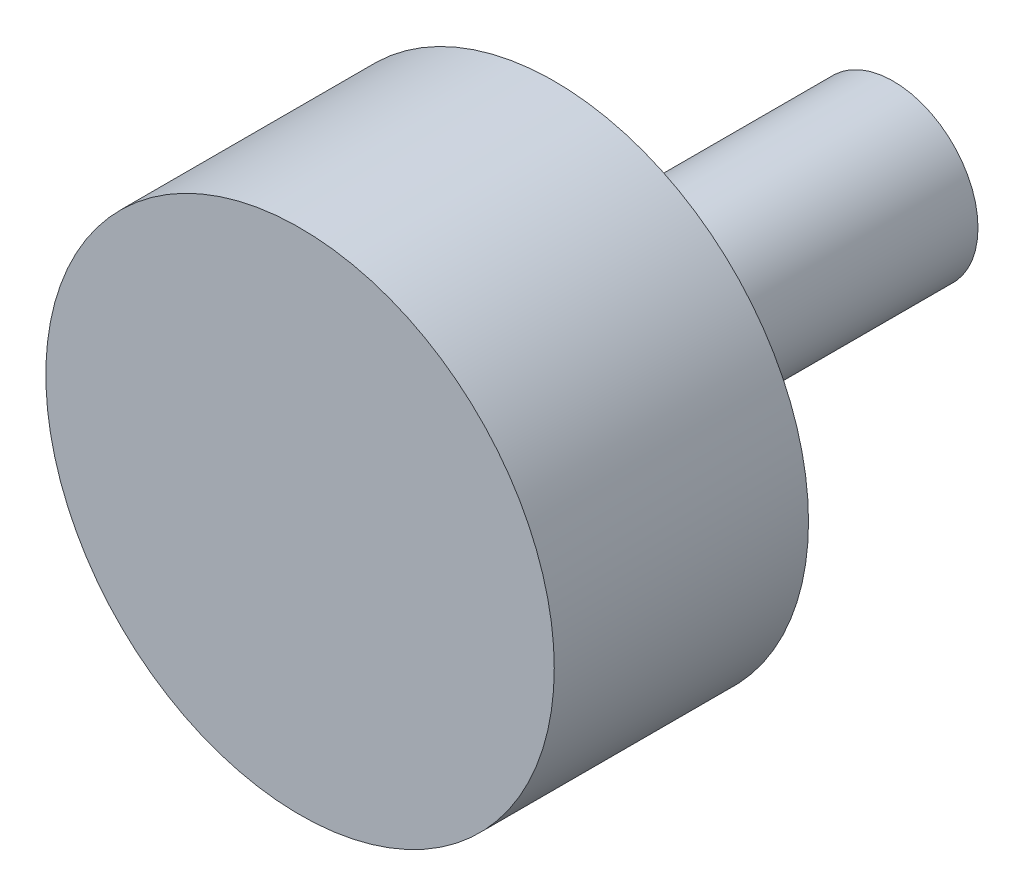
SolidWorks part; units mm, degrees
material "AISI 1035 Steel (SS)"
ref_plane "Front Plane" through (0, 0, 0) normal (0, 0, 1) x (1, 0, 0)
ref_plane "Top Plane" through (0, 0, 0) normal (0, 1, 0) x (1, 0, 0)
ref_plane "Right Plane" through (0, 0, 0) normal (1, 0, 0) x (0, 0, -1)
sketch "Sketch1" plane through (0, 0, 0) normal (0, 1, 0) x (1, 0, 0)
  line L0 (127, 508) -> (0, 508)
  line L1 (0, 508) -> (0, -381)
  line L2 (0, -381) -> (381, -381)
  line L3 (381, -381) -> (381, 0)
  line L4 (381, 0) -> (177.8, 0)
  line L5 (127, 50.8) -> (127, 508)
  line L6 (0, 508) -> (0, -381) construction
  arc A0 (177.8, 0) -> (127, 50.8) centre (177.8, 50.8) cw
revolve "Revolve1" add sketch "Sketch1" angle 360 about L6
